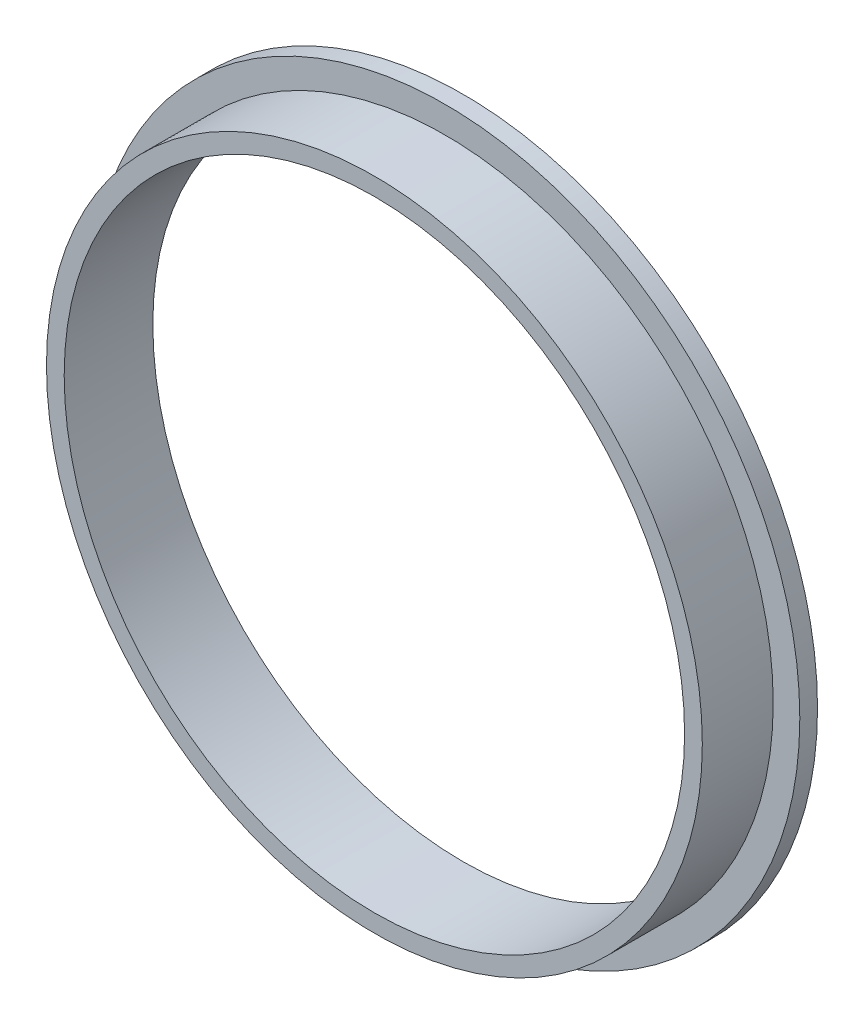
SolidWorks part; units mm, degrees
ref_plane "Front Plane" through (0, 0, 0) normal (0, 0, 1) x (1, 0, 0)
ref_plane "Top Plane" through (0, 0, 0) normal (0, 1, 0) x (1, 0, 0)
ref_plane "Right Plane" through (0, 0, 0) normal (1, 0, 0) x (0, 0, -1)
sketch "Esquisse1" plane through (0, 0, 0) normal (0, 0, 1) x (1, 0, 0)
  circle A0 centre (0, 0) radius 37
  circle A1 centre (0, 0) radius 35
extrude "Boss.-Extru.1" add sketch "Esquisse1" along normal blind 10
sketch "Esquisse3" plane through (0, 0, 0) normal (0, 0, 1) x (1, 0, 0)
  circle A0 centre (0, 0) radius 40
extrude "Boss.-Extru.2" add sketch "Esquisse3" along normal blind 2
sketch "Esquisse4" plane through (0, 0, 2) normal (0, 0, 1) x (1, 0, 0)
  circle A0 centre (0, 0) radius 35
extrude "Enlèv. mat.-Extru.1" cut sketch "Esquisse4" against normal blind 2
